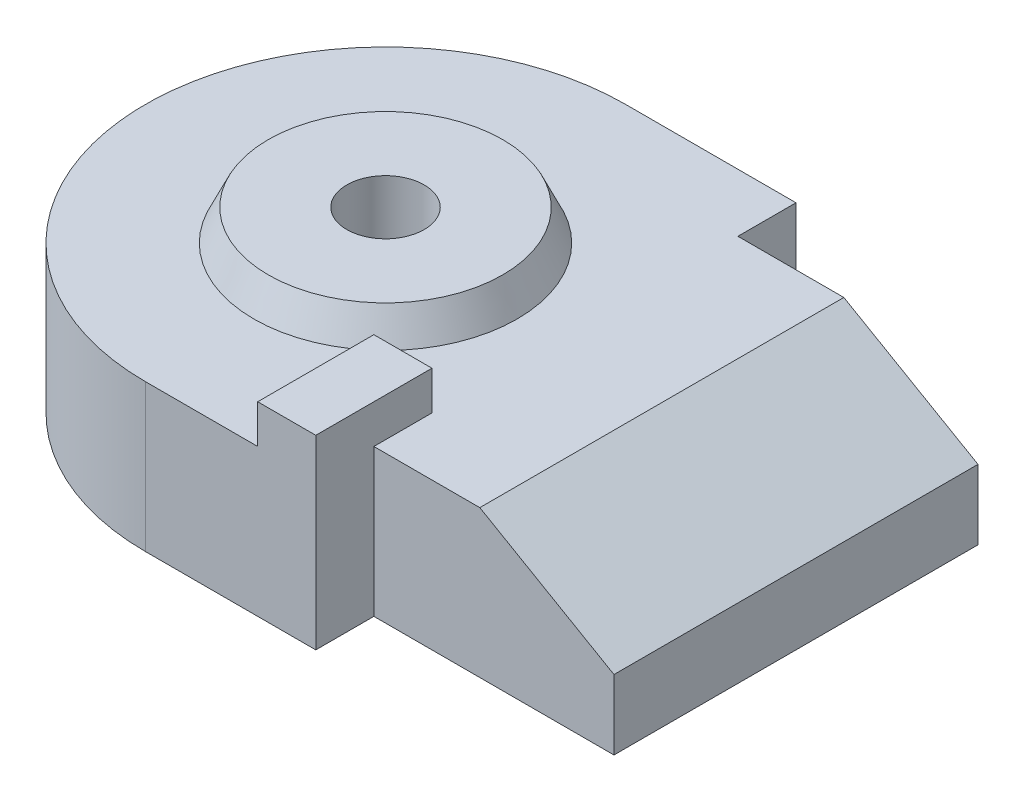
SolidWorks part; units mm, degrees
material "1060 Alloy"
ref_plane "Front Plane" through (0, 0, 0) normal (0, 0, 1) x (1, 0, 0)
ref_plane "Top Plane" through (0, 0, 0) normal (0, 1, 0) x (1, 0, 0)
ref_plane "Right Plane" through (0, 0, 0) normal (1, 0, 0) x (0, 0, -1)
sketch "Sketch1" plane through (0, 0, 0) normal (0, 1, 0) x (1, 0, 0)
  line L0 (0, 0) -> (0, -75)
  line L1 (0, -75) -> (-220, -75)
  line L2 (-220, 545) -> (0, 545)
  line L3 (0, 545) -> (0, 470)
  line L4 (0, 470) -> (310, 470)
  line L5 (310, 470) -> (310, 0)
  line L6 (310, 0) -> (0, 0)
  arc A0 (-220, -75) -> (-220, 545) centre (-220, 235) cw
  dimension "D3" = 310
  dimension "D1" = 530
  dimension "D2" = 310
  dimension "D4" = 75
  dimension "D5" = 75
extrude "Boss-Extrude1" add sketch "Sketch1" along normal blind 190
sketch "Sketch2" plane through (0, 190, 0) normal (0, 1, 0) x (1, 0, 0)
  circle A0 centre (-220, 235) radius 170
  dimension "D1" = 340
extrude "Boss-Extrude2" add sketch "Sketch2" along normal blind 40 draft 25
sketch "Sketch3" plane through (0, 190, 0) normal (0, 1, 0) x (1, 0, 0)
  line L1 (0, -75) -> (-75, -75)
  line L2 (0, -75) -> (0, 75)
  line L3 (0, 75) -> (-75, 75)
  line L4 (-75, -75) -> (-75, 75)
  dimension "D1" = 75
  dimension "D2" = 150
extrude "Boss-Extrude3" add sketch "Sketch3" along normal blind 50
sketch "Sketch4" plane through (0, 230, 0) normal (0, 1, 0) x (1, 0, 0)
  circle A0 centre (-220, 235) radius 50
  dimension "D1" = 100
extrude "Cut-Extrude1" cut sketch "Sketch4" against normal through all
sketch "Sketch5" plane through (0, 0, 0) normal (0, 0, 1) x (1, 0, 0)
  line L4 (136.7949, 190) -> (310, 90)
  line L8 (0, 0) -> (310, 0)
  line L9 (310, 0) -> (310, 190)
  line L10 (310, 190) -> (0, 190)
  line L11 (0, 190) -> (0, 0)
  line L12 (0, 0) -> (310, 0)
  line L13 (310, 0) -> (310, 190)
  line L14 (310, 190) -> (0, 190)
  line L15 (0, 190) -> (0, 0)
  line M7 (310, 0) -> (310, 190)
  line M8 (310, 190) -> (0, 190)
  dimension "D2" = 60
  dimension "D3" = 90
  dimension "D1" = 0
extrude "Cut-Extrude2" cut sketch "Sketch5" against normal through all contours L4 M8 M7
equation "\"B\"=530"
equation "\"D1@Sketch1\"=\"B\""
equation "\"C\"=310"
equation "\"D2@Sketch1\"=\"C\""
equation "\"A\"=310"
equation "\"D3@Sketch1\"=\"A\""
equation "\"D3@Boss-Extrude2\"=90-65"
